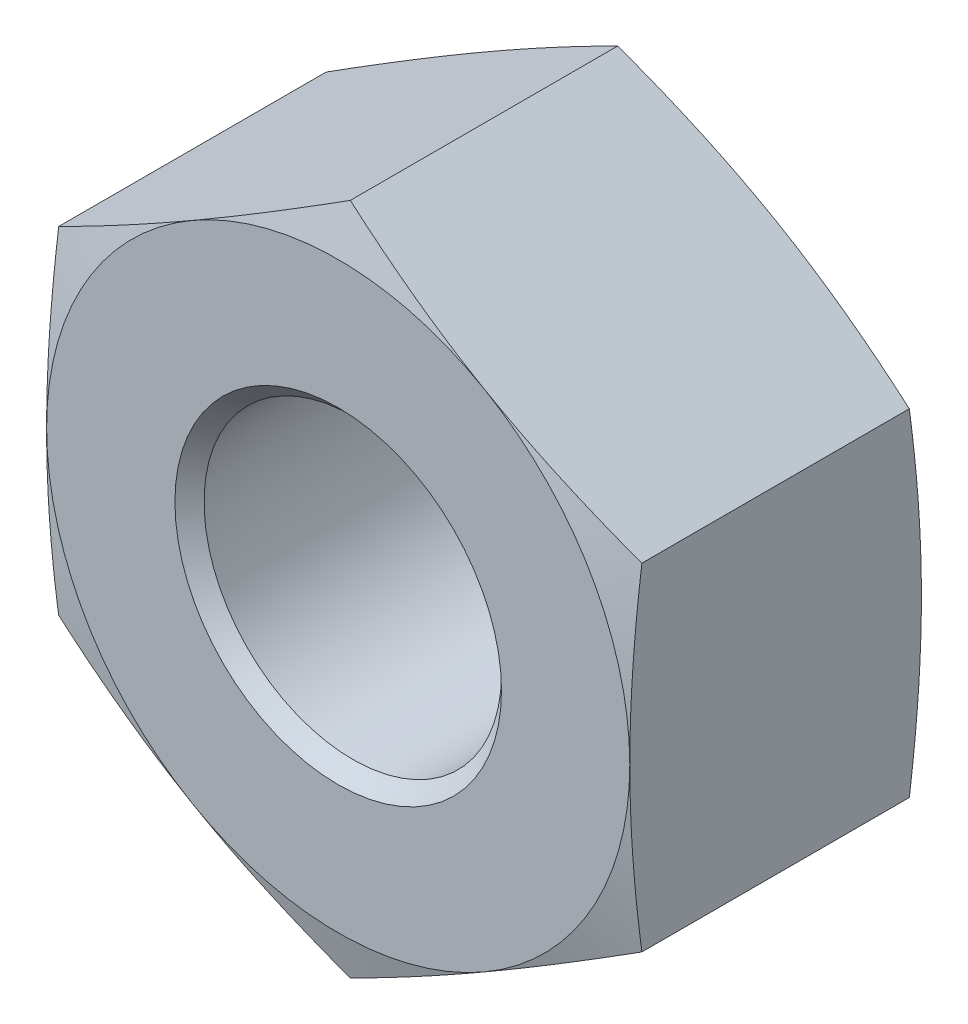
SolidWorks part; units mm, degrees
ref_plane "Plano frontal" through (0, 0, 0) normal (0, 0, 1) x (1, 0, 0)
ref_plane "Plano superior" through (0, 0, 0) normal (0, 1, 0) x (1, 0, 0)
ref_plane "Plano direito" through (0, 0, 0) normal (1, 0, 0) x (0, 0, -1)
sketch "Esboço1" plane through (0, 0, 0) normal (0, 0, 1) x (1, 0, 0)
  line L1 (0, 11.547) -> (-10, 5.7735)
  line L2 (-10, 5.7735) -> (-10, -5.7735)
  line L3 (-10, -5.7735) -> (0, -11.547)
  line L4 (0, -11.547) -> (10, -5.7735)
  line L5 (10, -5.7735) -> (10, 5.7735)
  line L6 (10, 5.7735) -> (0, 11.547)
  circle A0 centre (0, 0) radius 10 construction
  dimension "D1" = 20
extrude "Ressalto-extrusão1" add sketch "Esboço1" along normal blind 10
sketch "Esboço2" plane through (0, 0, 10) normal (0, 0, 1) x (1, 0, 0)
  circle A0 centre (0, 0) radius 10
extrude "Corte-extrusão1" cut sketch "Esboço2" against normal blind 15 draft 75 flip side to cut
sketch "Esboço3" plane through (0, 0, 0) normal (0, 0, -1) x (-1, 0, 0)
  circle A0 centre (0, 0) radius 10
extrude "Corte-extrusão2" cut sketch "Esboço3" against normal blind 15 draft 75 flip side to cut
hole_wizard "Furo roscado de M121" positions "Esboço5" profile "Esboço6" tap size "M12" standard "DIN" end condition through all
sketch "Esboço5" plane through (0, 0, 0) normal (0, 0, -1) x (-1, 0, 0)
  point P0 (0, 0)
sketch "Esboço6" plane through (0, 0, 0) normal (1, 0, 0) x (0, 1, 0)
  line L0 (0, 0) -> (0, 10)
  line L1 (0, 10) -> (5.1, 10)
  line L2 (5.1, 10) -> (5.1, 0)
  line L5 (5.1, 0) -> (0, 0)
  line L11 (0, -6.35) -> (0, 107.95) construction
  dimension "Thru Tap Drill Dia." = 10.2
  dimension "Thru Tap Drill Depth" = 10
cosmetic thread "Rosca de furo1" parameters "D2"=12
cosmetic thread "Representação de rosca1" parameters "D2"=12
chamfer "Chanfro3" distance 0.5 angle 45 1 edges at (-5.1, 0, 10)
chamfer "Chanfro4" distance 0.5 angle 45 1 edges at (-5.1, 0, 0)
